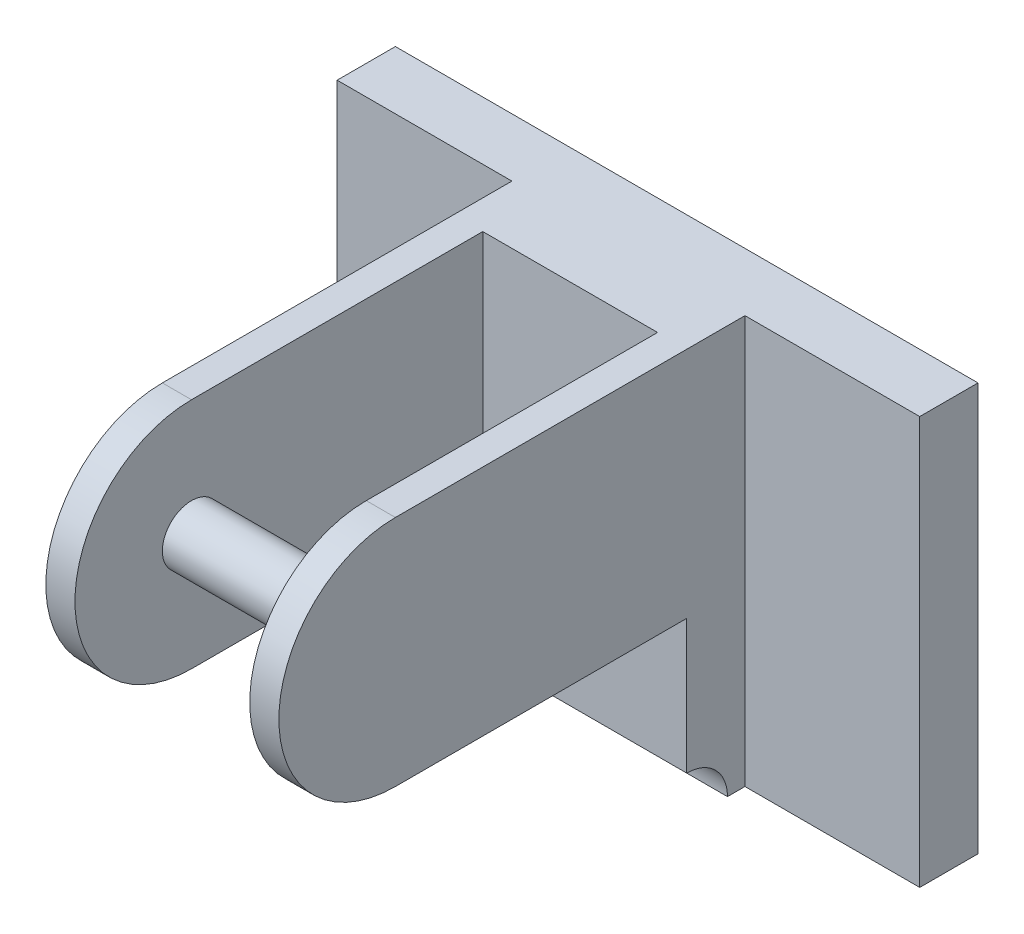
SolidWorks part; units mm, degrees
ref_plane "前基準面" through (0, 0, 0) normal (0, 0, 1) x (1, 0, 0)
ref_plane "上基準面" through (0, 0, 0) normal (0, 1, 0) x (1, 0, 0)
ref_plane "右基準面" through (0, 0, 0) normal (1, 0, 0) x (0, 0, -1)
sketch "草圖1" plane through (0, 0, 0) normal (0, 0, 1) x (1, 0, 0)
  line L1 (50, 35) -> (-50, 35)
  line L2 (50, 35) -> (50, -35)
  line L3 (50, -35) -> (-50, -35)
  line L4 (-50, 35) -> (-50, -35)
  line L5 (50, 35) -> (-50, -35) construction
  line L6 (50, -35) -> (-50, 35) construction
  point P0 (0, 0)
  dimension "D1" = 100
  dimension "D2" = 70
extrude "填料-伸長1" add sketch "草圖1" along normal blind 10
sketch "草圖2" plane through (0, 0, 10) normal (0, 0, 1) x (1, 0, 0)
  line L0 (50, 35) -> (-50, 35) construction
  line L1 (20, -35) -> (-20, -35)
  line L2 (20, -35) -> (20, 35)
  line L3 (20, 35) -> (-20, 35)
  line L4 (-20, -35) -> (-20, 35)
  line L5 (20, -35) -> (-20, 35) construction
  line L6 (20, 35) -> (-20, -35) construction
  line L7 (50, -35) -> (50, 35) construction
  point P0 (0, 0)
  dimension "D1" = 40
  dimension "D2" = 30
extrude "填料-伸長2" add sketch "草圖2" along normal blind 10
sketch "草圖3" plane through (20, 0, 0) normal (1, 0, 0) x (0, 0, -1)
  line L0 (-20, -35) -> (-20, 35) construction
  line L1 (-20, -35) -> (-10, -35) construction
  line L2 (-20, -35) -> (-20, -28)
  line L3 (-20, -35) -> (-13, -35)
  arc A0 (-20, -28) -> (-13, -35) centre (-20, -35) cw
  dimension "D1" = 7
extrude "除料-伸長1" cut sketch "草圖3" against normal through all
sketch "草圖4" plane through (20, 0, 0) normal (1, 0, 0) x (0, 0, -1)
  line L1 (-20, 35) -> (-70, 35)
  line L2 (-20, 35) -> (-20, -5)
  line L3 (-20, -5) -> (-70, -5)
  line L4 (-70, 35) -> (-70, -5)
  arc A0 (-70, 35) -> (-70, -5) centre (-70, 15) ccw
  line M5 (-20, 35) -> (-20, -28)
  dimension "D1" = 50
  dimension "D2" = 40
extrude "填料-伸長3" add sketch "草圖4" against normal blind 5 contours L1 L4 L3 M5 | L4 A0
sketch "草圖5" plane through (-20, 0, 0) normal (-1, 0, 0) x (0, 0, 1)
  line L1 (20, 35) -> (70, 35)
  line L2 (20, 35) -> (20, -5)
  line L3 (20, -5) -> (70, -5)
  line L4 (70, 35) -> (70, -5)
  arc A0 (70, -5) -> (70, 35) centre (70, 15) ccw
  line M7 (20, -28) -> (20, 35)
  dimension "D1" = 40
  dimension "D2" = 50
extrude "填料-伸長4" add sketch "草圖5" against normal blind 5 contours L4 L1 L3 M7 | L4 A0
sketch "草圖6" plane through (-15, 0, 0) normal (1, 0, 0) x (0, 0, -1)
  line L0 (-70, 35) -> (-70, 22.825) construction
  line L1 (-86.5715, 15) -> (-50.3383, 15) construction
  line L4 (-20, 35) -> (-70, 35) construction
  line L5 (-20, -5) -> (-70, -5) construction
  circle A0 centre (-70, 15) radius 5
  point P0 (-70, 15)
  dimension "D1" = 10
extrude "填料-伸長5" add sketch "草圖6" along normal up to surface (30 mm away) up to face at (15, 15, 50)
